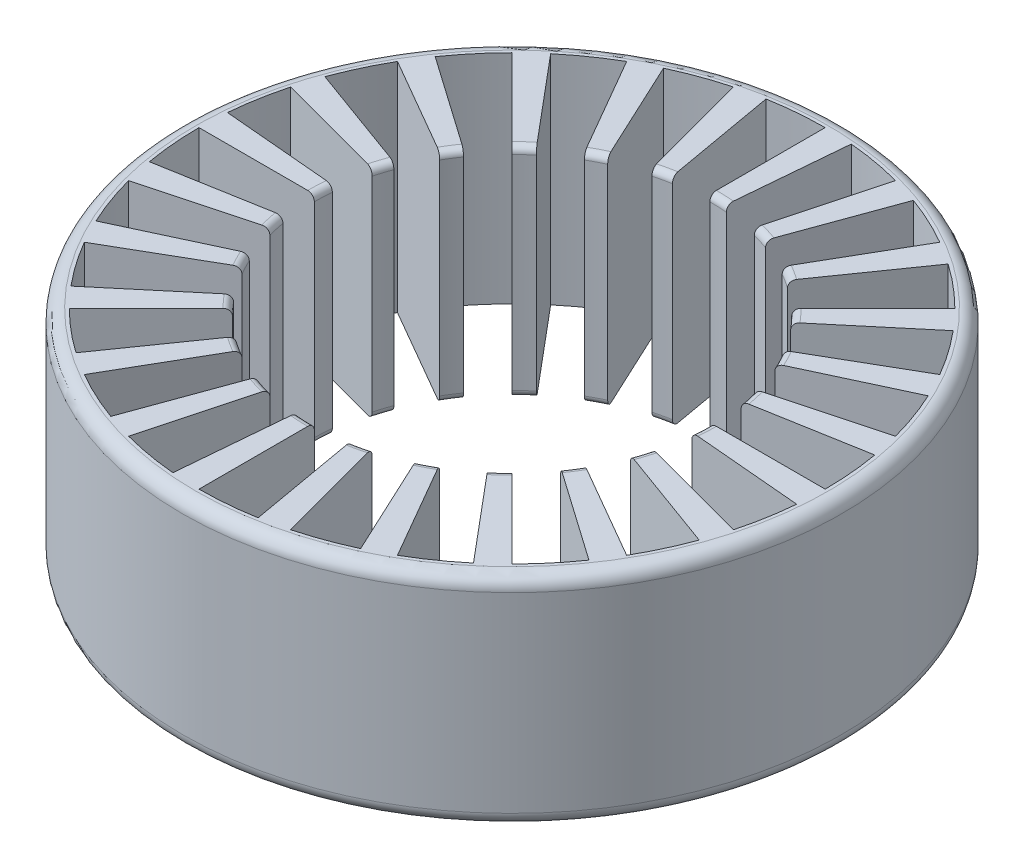
SolidWorks part; units mm, degrees
ref_plane "前视基准面" through (0, 0, 0) normal (0, 0, 1) x (1, 0, 0)
ref_plane "上视基准面" through (0, 0, 0) normal (0, 1, 0) x (1, 0, 0)
ref_plane "右视基准面" through (0, 0, 0) normal (1, 0, 0) x (0, 0, -1)
sketch "草图1" plane through (0, 0, 0) normal (0, 1, 0) x (1, 0, 0)
  circle A1 centre (0, 0) radius 25
  dimension "D2" = 50
extrude "凸台-拉伸1" add sketch "草图1" along normal blind 16.5 contours A1
sketch "草图2" plane through (0, 0, 0) normal (0, -1, 0) x (1, 0, 0)
  circle A0 centre (0, 0) radius 15
  dimension "D1" = 30
extrude "切除-拉伸2" cut sketch "草图2" against normal blind 19 contours A0
sketch "草图3" plane through (0, 0, 0) normal (0, -1, 0) x (1, 0, 0)
  line L0 (0, 0) -> (0, 23.75)
  line L1 (0, 23.75) -> (0, 0)
  line L2 (0, 0) -> (4.1241, 23.3892)
  line L3 (0, 0) -> (6.147, 22.9407)
  line L4 (0, 0) -> (10.0372, 21.5248)
  line L5 (0, 0) -> (11.875, 20.5681)
  line L6 (0, 0) -> (15.2662, 18.1936)
  line L7 (0, 0) -> (16.7938, 16.7938)
  line L8 (0, 0) -> (19.4549, 13.6224)
  line L9 (0, 0) -> (20.5681, 11.875)
  line L10 (0, 0) -> (22.3177, 8.123)
  line L11 (0, 0) -> (22.9407, 6.147)
  line L12 (0, 0) -> (23.6596, 2.0699)
  line L13 (0, 0) -> (23.75, 0)
  line L14 (0, 0) -> (23.3892, -4.1241)
  line L15 (0, 0) -> (22.9407, -6.147)
  line L16 (0, 0) -> (21.5248, -10.0372)
  line L17 (0, 0) -> (20.5681, -11.875)
  line L18 (0, 0) -> (18.1936, -15.2662)
  line L19 (0, 0) -> (16.7938, -16.7938)
  line L20 (0, 0) -> (13.6224, -19.4549)
  line L21 (0, 0) -> (11.875, -20.5681)
  line L22 (0, 0) -> (8.123, -22.3177)
  line L23 (0, 0) -> (6.147, -22.9407)
  line L24 (0, 0) -> (2.0699, -23.6596)
  line L25 (0, 0) -> (0, -23.75)
  line L26 (0, 0) -> (-4.1241, -23.3892)
  line L27 (0, 0) -> (-6.147, -22.9407)
  line L28 (0, 0) -> (-10.0372, -21.5248)
  line L29 (0, 0) -> (-11.875, -20.5681)
  line L30 (0, 0) -> (-15.2662, -18.1936)
  line L31 (0, 0) -> (-16.7938, -16.7938)
  line L32 (0, 0) -> (-19.4549, -13.6224)
  line L33 (0, 0) -> (-20.5681, -11.875)
  line L34 (0, 0) -> (-22.3177, -8.123)
  line L35 (0, 0) -> (-22.9407, -6.147)
  line L36 (0, 0) -> (-23.6596, -2.0699)
  line L37 (0, 0) -> (-23.75, 0)
  line L38 (0, 0) -> (-23.3892, 4.1241)
  line L39 (0, 0) -> (-22.9407, 6.147)
  line L40 (0, 0) -> (-21.5248, 10.0372)
  line L41 (0, 0) -> (-20.5681, 11.875)
  line L42 (0, 0) -> (-18.1936, 15.2662)
  line L43 (0, 0) -> (-16.7938, 16.7938)
  line L44 (0, 0) -> (-13.6224, 19.4549)
  line L45 (0, 0) -> (-11.875, 20.5681)
  line L46 (0, 0) -> (-8.123, 22.3177)
  line L47 (0, 0) -> (-6.147, 22.9407)
  line L48 (0, 0) -> (-2.0699, 23.6596)
  circle A0 centre (0, 0) radius 23.75
  circle M4 centre (0, 0) radius 15
  dimension "D1" = 47.5
  dimension "D2" = 10
  dimension "D3" = 24
extrude "切除-拉伸3" cut sketch "草图3" against normal blind 19 contours L42 A0 L41 M4 | L44 A0 L43 M4 | L46 A0 L45 M4 | L48 A0 L47 M4 | L2 A0 L0 M4 | L4 A0 L3 M4 | L6 A0 L5 M4 | L8 A0 L7 M4 | L10 A0 L9 M4 | L12 A0 L11 M4 | L14 A0 L13 M4 | L16 A0 L15 M4 | L18 A0 L17 M4 | L20 A0 L19 M4 | L22 A0 L21 M4 | L24 A0 L23 M4 | L26 A0 L25 M4 | L28 A0 L27 M4 | L30 A0 L29 M4 | L32 A0 L31 M4 | L34 A0 L33 M4 | L36 A0 L35 M4 | L38 A0 L37 M4 | L40 A0 L39 M4
fillet "圆角1" radius 1 1 edges at (0, 0, 25)
fillet "圆角2" radius 1 1 edges at (0, 16.5, 25)
fillet "圆角3" radius 0.5 24 edges at (-8.0595, 16.5, 12.6509) (-4.5106, 16.5, 14.3058) (-0.6543, 16.5, 14.9857) (3.2466, 16.5, 14.6444) (6.9262, 16.5, 13.3052) (10.1339, 16.5, 11.0592) (12.6509, 16.5, 8.0595) (14.3058, 16.5, 4.5106) (14.9857, 16.5, 0.6543) (14.6444, 16.5, -3.2466) (13.3052, 16.5, -6.9262) (11.0592, 16.5, -10.1339) (8.0595, 16.5, -12.6509) (4.5106, 16.5, -14.3058) (0.6543, 16.5, -14.9857) (-3.2466, 16.5, -14.6444) (-6.9262, 16.5, -13.3052) (-10.1339, 16.5, -11.0592) (-12.6509, 16.5, -8.0595) (-14.3058, 16.5, -4.5106) (-14.9857, 16.5, -0.6543) (-14.6444, 16.5, 3.2466) (-13.3052, 16.5, 6.9262) (-11.0592, 16.5, 10.1339)
fillet "圆角4" radius 0.5 24 edges at (4.5106, 0, -14.3058) (0.6543, 0, -14.9857) (-3.2466, 0, -14.6444) (-6.9262, 0, -13.3052) (-10.1339, 0, -11.0592) (-12.6509, 0, -8.0595) (-14.3058, 0, -4.5106) (-14.9857, 0, -0.6543) (-14.6444, 0, 3.2466) (-13.3052, 0, 6.9262) (-11.0592, 0, 10.1339) (-8.0595, 0, 12.6509) (-4.5106, 0, 14.3058) (-0.6543, 0, 14.9857) (3.2466, 0, 14.6444) (6.9262, 0, 13.3052) (10.1339, 0, 11.0592) (12.6509, 0, 8.0595) (14.3058, 0, 4.5106) (14.9857, 0, 0.6543) (14.6444, 0, -3.2466) (13.3052, 0, -6.9262) (11.0592, 0, -10.1339) (8.0595, 0, -12.6509)
